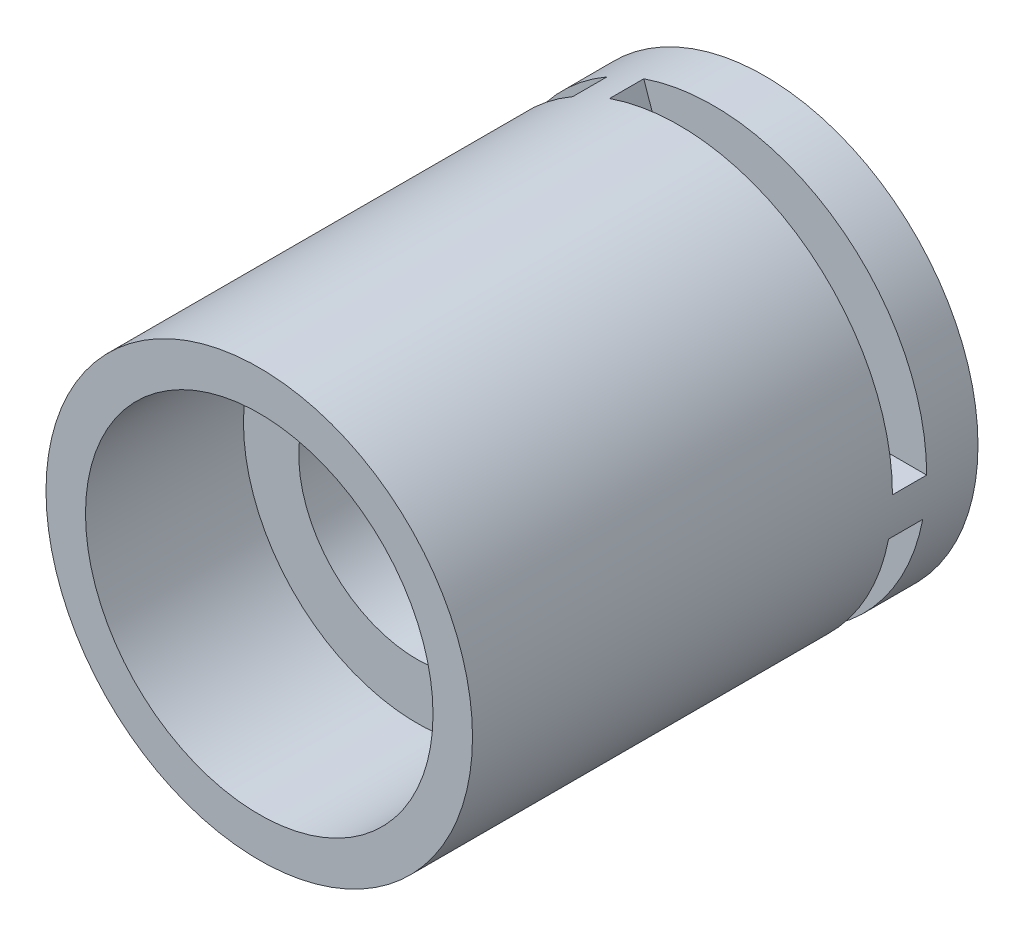
SolidWorks part; units mm, degrees
ref_plane "Front Plane" through (0, 0, 0) normal (0, 0, 1) x (1, 0, 0)
ref_plane "Top Plane" through (0, 0, 0) normal (0, 1, 0) x (1, 0, 0)
ref_plane "Right Plane" through (0, 0, 0) normal (1, 0, 0) x (0, 0, -1)
sketch "Sketch2" plane through (0, 0, 0) normal (0, 0, 1) x (1, 0, 0)
  circle A0 centre (0, 0) radius 13.5
  dimension "D1" = 27
extrude "Boss-Extrude1" add sketch "Sketch2" against normal blind 32
ref_plane "Plane1" through (0, 0, 0) normal (0, 0, 1) x (1, 0, 0)
sketch "Sketch4" plane through (0, 0, 0) normal (0, 0, 1) x (1, 0, 0)
  circle A0 centre (0, 0) radius 11
  dimension "D1" = 22
extrude "Cut-Extrude1" cut sketch "Sketch4" against normal blind 10
sketch "Sketch5" plane through (0, 0, 0) normal (0, 0, 1) x (1, 0, 0)
  circle A0 centre (0, 0) radius 7.5
  dimension "D1" = 15
extrude "Cut-Extrude2" cut sketch "Sketch5" against normal blind 30
sketch "Sketch9" plane through (0, 0, -32) normal (0, 0, -1) x (-1, 0, 0)
  line L0 (0, -18.8285) -> (0, 25.3406) construction
sketch3d "3DSketch4"
  point P0 (4.7437, 12.6391, -18.7172)
ref_plane "Plane5" through (0, 13.5, 0) normal (0, 1, 0) x (1, 0, 0)
sketch "Sketch10" plane through (0, 13.5, 0) normal (0, 1, 0) x (1, 0, 0)
  line L0 (13.5, 32) -> (-13.5, 32) construction
  line L1 (-4.4913, 28.75) -> (21.2187, 28.75)
  line L2 (-4.4913, 28.75) -> (-4.4913, 26.584)
  line L3 (-4.4913, 26.584) -> (21.2187, 26.584)
  line L4 (21.2187, 28.75) -> (21.2187, 26.584)
  dimension "D1" = 25.71
  dimension "D2" = 2.166
  dimension "D3" = 3.25
wrap "Wrap1" sketch "Sketch10" wrap type deboss source sketch "Sketch10" thickness 12 face at (13.5, 0, -32) parameters "D1"=12
pattern_circular "CirPattern1" count 3 over 360 about axis through (0, 0, 0) along (0, 0, 1) of "Wrap1"
